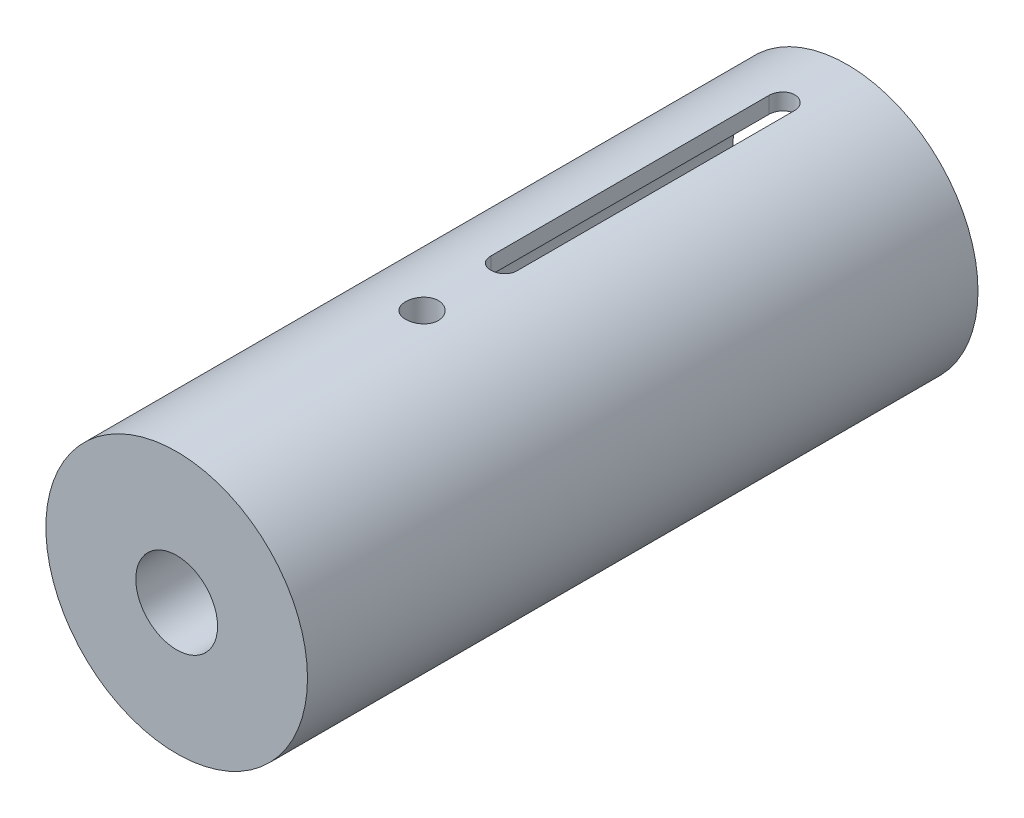
SolidWorks part; units mm, degrees
ref_plane "Front Plane" through (0, 0, 0) normal (0, 0, 1) x (1, 0, 0)
ref_plane "Top Plane" through (0, 0, 0) normal (0, 1, 0) x (1, 0, 0)
ref_plane "Right Plane" through (0, 0, 0) normal (1, 0, 0) x (0, 0, -1)
sketch "Sketch1" plane through (0, 0, 0) normal (0, 0, 1) x (1, 0, 0)
  circle A0 centre (0, 0) radius 7
  circle A1 centre (0, 0) radius 8
  dimension "D1" = 16
  dimension "D2" = 14
extrude "Boss-Extrude1" add sketch "Sketch1" along normal blind 41
sketch "Sketch2" plane through (0, 0, 0) normal (0, 1, 0) x (1, 0, 0)
  line L0 (8, 0) -> (-8, 0) construction
  line L2 (-0.7937, -4) -> (-0.7938, -21)
  line L4 (0.7937, -4) -> (0.7938, -21)
  arc A0 (-0.7937, -4) -> (0.7937, -4) centre (0, -4) cw
  arc A1 (-0.7938, -21) -> (0.7938, -21) centre (0, -21) ccw
  dimension "D1" = 1.5875
  dimension "D2" = 17
  dimension "D3" = 21
extrude "Cut-Extrude1" cut sketch "Sketch2" against normal through all and the other way through all
sketch "Sketch3" plane through (0, 0, 41) normal (0, 0, 1) x (1, 0, 0)
  circle A0 centre (0, 0) radius 7
  circle A1 centre (0, 0) radius 2.5
  dimension "D1" = 5
  dimension "D2" = 14
extrude "Boss-Extrude2" add sketch "Sketch3" against normal blind 17
sketch "Sketch4" plane through (0, 0, 0) normal (0, 1, 0) x (1, 0, 0)
  line L0 (-2.5, -41) -> (2.5, -41) construction
  line L1 (-2.5, -41) -> (2.5, -41) construction
  circle A0 centre (0, -26) radius 1
  dimension "D1" = 2
  dimension "D2" = 15
extrude "Cut-Extrude2" cut sketch "Sketch4" along normal blind 17
